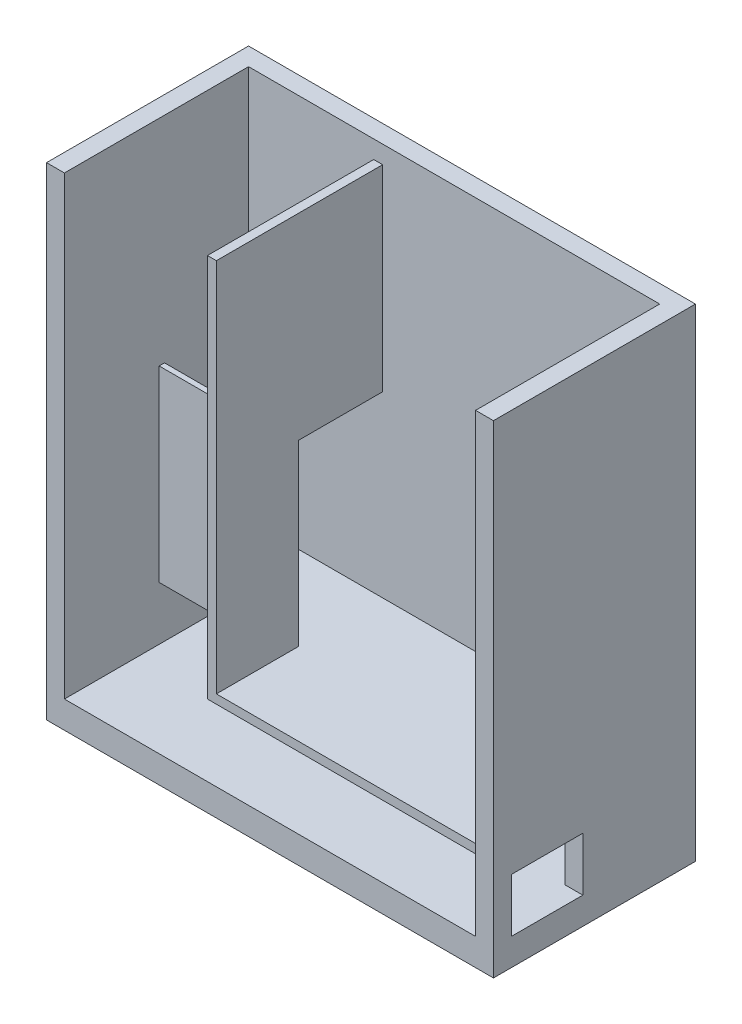
SolidWorks part; units mm, degrees
ref_plane "Front Plane" through (0, 0, 0) normal (0, 0, 1) x (1, 0, 0)
ref_plane "Top Plane" through (0, 0, 0) normal (0, 1, 0) x (1, 0, 0)
ref_plane "Right Plane" through (0, 0, 0) normal (1, 0, 0) x (0, 0, -1)
sketch "Sketch1" plane through (0, 0, 0) normal (0, 0, 1) x (1, 0, 0)
  line L1 (0, 0) -> (125, 0)
  line L2 (0, 0) -> (0, 135)
  line L3 (0, 135) -> (125, 135)
  line L4 (125, 0) -> (125, 135)
  dimension "D1" = 125
  dimension "D2" = 135
extrude "Boss-Extrude1" add sketch "Sketch1" along normal blind 5 contours L2 L3 L4 L1
sketch "Sketch2" plane through (0, 0, 5) normal (0, 0, 1) x (1, 0, 0)
  line L0 (0, 0) -> (125, 0) construction
  line L1 (0, 135) -> (5, 135)
  line L2 (0, 135) -> (0, 0)
  line L3 (0, 0) -> (5, 0)
  line L4 (5, 135) -> (5, 0)
  dimension "D1" = 5
extrude "Boss-Extrude2" add sketch "Sketch2" along normal blind 51.5
sketch "Sketch3" plane through (0, 0, 5) normal (0, 0, 1) x (1, 0, 0)
  line L0 (125, 0) -> (125, 135) construction
  line L1 (125, 135) -> (120, 135)
  line L2 (125, 135) -> (125, 0)
  line L3 (125, 0) -> (120, 0)
  line L4 (120, 135) -> (120, 0)
  line L5 (5, 0) -> (125, 0) construction
  dimension "D1" = 5
extrude "Boss-Extrude3" add sketch "Sketch3" along normal blind 51.5
sketch "Sketch5" plane through (0, 0, 5) normal (0, 0, 1) x (1, 0, 0)
  line L0 (120, 135) -> (120, 0) construction
  line L1 (5, 0) -> (120, 0)
  line L2 (5, 0) -> (5, 7.57)
  line L3 (5, 7.57) -> (120, 7.57)
  line L4 (120, 0) -> (120, 7.57)
  dimension "D1" = 7.57
extrude "Boss-Extrude4" add sketch "Sketch5" along normal blind 51.5 contours L3 L4 L1 L2
sketch "Sketch21" plane through (0, 0, 5) normal (0, 0, 1) x (1, 0, 0)
  line L0 (5, 135) -> (120, 135) construction
  line L1 (40, 130) -> (42.5, 130)
  line L2 (40, 130) -> (40, 75)
  line L3 (40, 75) -> (42.5, 75)
  line L4 (42.5, 130) -> (42.5, 75)
  line L5 (5, 7.57) -> (5, 135) construction
  dimension "D1" = 2.5
  dimension "D2" = 55
  dimension "D3" = 5
  dimension "D4" = 35
extrude "Boss-Extrude13" add sketch "Sketch21" along normal blind 46.5
sketch "Sketch23" plane through (0, 0, 5) normal (0, 0, 1) x (1, 0, 0)
  line L0 (120, 135) -> (120, 7.57) construction
  line L1 (5, 25.07) -> (120, 25.07)
  line L2 (5, 25.07) -> (5, 22.57)
  line L3 (5, 22.57) -> (120, 22.57)
  line L4 (120, 25.07) -> (120, 22.57)
  line L5 (5, 7.57) -> (5, 135) construction
  line L6 (5, 7.57) -> (120, 7.57) construction
  dimension "D1" = 0
  dimension "D2" = 2.5
  dimension "D3" = 15
extrude "Boss-Extrude14" add sketch "Sketch23" along normal blind 25
sketch "Sketch24" plane through (0, 25.07, 0) normal (0, 1, 0) x (1, 0, 0)
  line L0 (5, -30) -> (5, -5) construction
  line L1 (5, -28.5) -> (40, -28.5)
  line L2 (5, -28.5) -> (5, -30)
  line L3 (5, -30) -> (40, -30)
  line L4 (40, -28.5) -> (40, -30)
  line L5 (120, -30) -> (5, -30) construction
  dimension "D1" = 35
  dimension "D2" = 1.5
extrude "Boss-Extrude15" add sketch "Sketch24" along normal up to surface (104.93 mm away) contours L1 L4 L3 L2 up to face at (41.25, 130, 28.25)
sketch "Sketch25" plane through (0, 0, 30) normal (0, 0, 1) x (1, 0, 0)
  line L1 (40, 25.07) -> (120, 25.07)
  line L2 (40, 25.07) -> (40, 22.57)
  line L3 (40, 22.57) -> (120, 22.57)
  line L4 (120, 25.07) -> (120, 22.57)
extrude "Boss-Extrude16" add sketch "Sketch25" along normal up to surface (26.5 mm away) up to face at (62.5, 69.3925, 56.5)
sketch "Sketch27" plane through (0, 25.07, 0) normal (0, 1, 0) x (1, 0, 0)
  line L0 (5, -28.5) -> (40, -28.5) construction
  line L1 (40, -56.5) -> (42.5, -56.5)
  line L2 (40, -56.5) -> (40, -28.5)
  line L3 (40, -28.5) -> (42.5, -28.5)
  line L4 (42.5, -56.5) -> (42.5, -28.5)
  dimension "D1" = 2.5
  dimension "D2" = 0
extrude "Boss-Extrude20" add sketch "Sketch27" along normal up to surface (104.93 mm away) contours L4 L3 L2 L1 up to face at (31.875, 130, 28.75)
sketch "Sketch28" plane through (0, 0, 30) normal (0, 0, 1) x (1, 0, 0)
  line L0 (40, 130) -> (40, 22.57) construction
  line L1 (5, 130) -> (40, 130)
  line L2 (5, 130) -> (5, 75)
  line L3 (5, 75) -> (40, 75)
  line L4 (40, 130) -> (40, 75)
  dimension "D1" = 55
extrude "Cut-Extrude1" cut sketch "Sketch28" against normal up to next contours L1 L4 L3 L2
sketch "Sketch29" plane through (0, 22.57, 0) normal (0, -1, 0) x (1, 0, 0)
  line L0 (40, 56.5) -> (40, 30) construction
  line L1 (120, 56.5) -> (40, 56.5)
  line L2 (120, 56.5) -> (120, 51.5)
  line L3 (120, 51.5) -> (40, 51.5)
  line L4 (40, 56.5) -> (40, 51.5)
  dimension "D1" = 5
extrude "Cut-Extrude2" cut sketch "Sketch29" against normal through all contours L3 L4 L1 L2
sketch "Sketch35" plane through (125, 0, 0) normal (1, 0, 0) x (0, 0, -1)
  line L0 (-51.5, 22.57) -> (-5, 22.57) construction
  line L1 (-31.5, 7.57) -> (-51.5, 7.57)
  line L2 (-31.5, 7.57) -> (-31.5, 22.57)
  line L3 (-31.5, 22.57) -> (-51.5, 22.57)
  line L4 (-51.5, 7.57) -> (-51.5, 22.57)
  line L5 (-56.5, 7.57) -> (-5, 7.57) construction
  line L6 (-5, 22.57) -> (-5, 7.57) construction
  dimension "D1" = 0
  dimension "D2" = 0
  dimension "D3" = 26.5
  dimension "D4" = 20
extrude "Cut-Extrude5" cut sketch "Sketch35" against normal blind 7.5
